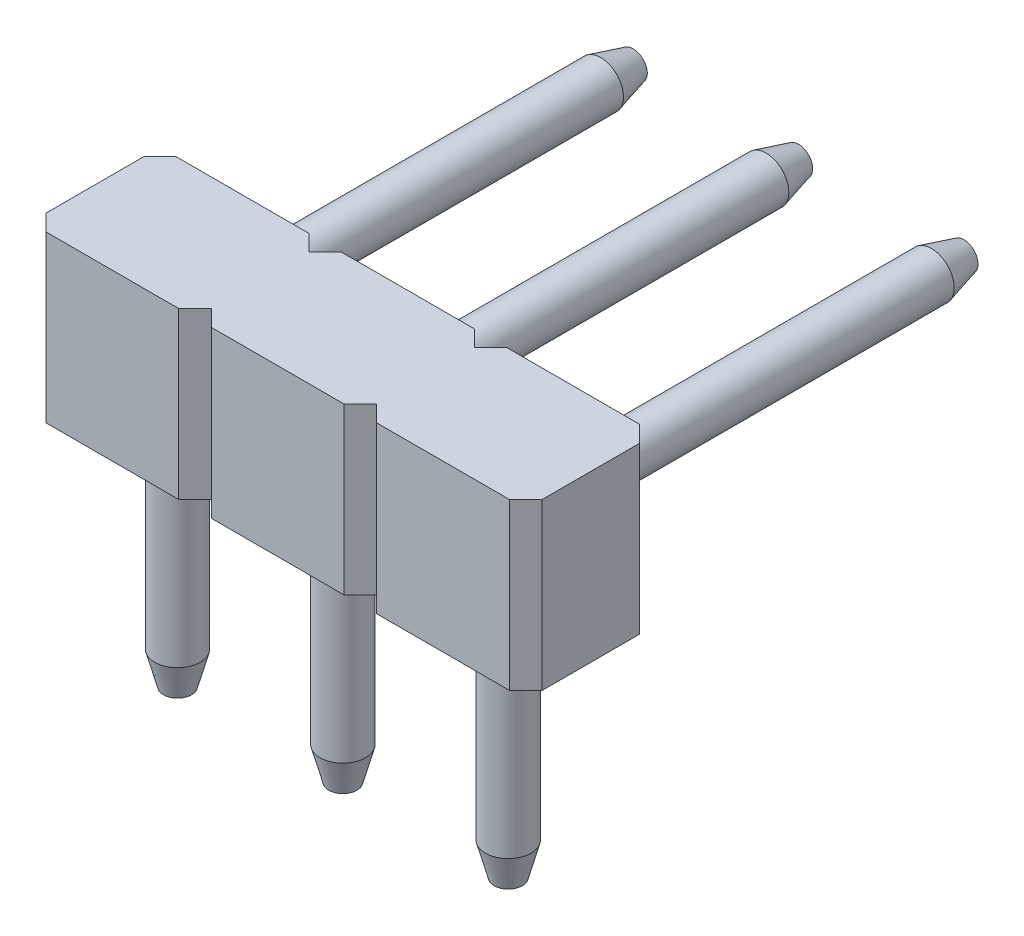
SolidWorks part; units mm, degrees
ref_plane "Plan de face" through (0, 0, 0) normal (0, 0, 1) x (1, 0, 0)
ref_plane "Plan de dessus" through (0, 0, 0) normal (0, 1, 0) x (1, 0, 0)
ref_plane "Plan de droite" through (0, 0, 0) normal (1, 0, 0) x (0, 0, -1)
sketch "Esquisse1" plane through (0, 0, 0) normal (0, 1, 0) x (1, 0, 0)
  circle A0 centre (0, 0) radius 0.35
  circle A1 centre (2.54, 0) radius 0.35
  circle A2 centre (5.08, 0) radius 0.35
  dimension "D1" = 0.7
  dimension "D2" = 3
extrude "Boss.-Extru.1" add sketch "Esquisse1" along normal blind 1 and the other way blind 3.5
chamfer "Chanfrein1" distance 0.5 angle 15 2 edges at (0, 1, 0.35) (0, -3.5, 0.35)
chamfer "Chanfrein2" distance 0.5 angle 15 2 edges at (2.54, -3.5, 0.35) (2.54, 1, 0.35)
chamfer "Chanfrein3" distance 0.5 angle 15 2 edges at (5.08, 1, 0.35) (5.08, -3.5, 0.35)
sketch "Esquisse2" plane through (0, 0, 0) normal (0, 1, 0) x (1, 0, 0)
  line L0 (-1.27, 0.75) -> (-1.02, 1)
  line L1 (-1.02, 1) -> (1.02, 1)
  line L2 (-1.27, 0.75) -> (-1.27, -0.75)
  line L3 (-1.02, -1) -> (1.0167, -1)
  line L5 (1.02, 1) -> (1.27, 0.75)
  line L6 (1.27, -0.75) -> (1.0167, -1)
  line L7 (-1.27, -0.75) -> (-1.02, -1)
  line L8 (1.27, 0.75) -> (1.52, 1)
  line L9 (1.52, 1) -> (3.56, 1)
  line L11 (1.52, -1) -> (3.5567, -1)
  line L13 (3.56, 1) -> (3.81, 0.75)
  line L14 (3.81, -0.75) -> (3.5567, -1)
  line L15 (1.27, -0.75) -> (1.52, -1)
  line L16 (3.81, 0.75) -> (4.06, 1)
  line L17 (4.06, 1) -> (6.1, 1)
  line L19 (4.06, -1) -> (6.0967, -1)
  line L20 (6.35, 0.75) -> (6.35, -0.75)
  line L21 (6.1, 1) -> (6.35, 0.75)
  line L22 (6.35, -0.75) -> (6.0967, -1)
  line L23 (3.81, -0.75) -> (4.06, -1)
  line L25 (3.81, 0.75) -> (3.81, -0.75) [skipped]
  line L26 (1.27, 0.75) -> (1.27, -0.75) [skipped]
  point P0 (-1.27, 1)
  point P1 (1.2667, -1)
  point P2 (-1.27, -1)
  point P3 (1.27, 1)
  point P14 (1.27, 1)
  point P15 (3.8067, -1)
  point P16 (1.27, -1)
  point P17 (3.81, 1)
  point P26 (3.81, 1)
  point P27 (6.3467, -1)
  point P28 (3.81, -1)
  point P29 (6.35, 1)
  dimension "D1" = 1.27
  dimension "D2" = 2.54
  dimension "D3" = 1
  dimension "D4" = 2
  dimension "D5" = 3
extrude "Boss.-Extru.2" add sketch "Esquisse2" along normal blind 2.54
sketch "Esquisse3" plane through (0, 0, -1) normal (0, 0, -1) x (-1, 0, 0)
  line L1 (-6.1, 0) -> (-4.06, 0) construction
  line L2 (-6.35, 2.54) -> (-6.35, 0) construction
  circle A0 centre (-5.08, 1.27) radius 0.35
  circle A1 centre (-2.54, 1.27) radius 0.35
  circle A2 centre (0, 1.27) radius 0.35
  dimension "D1" = 1.27
  dimension "D2" = 1.27
  dimension "D4" = 0.7
  dimension "D3" = 3
extrude "Boss.-Extru.3" add sketch "Esquisse3" along normal blind 6
chamfer "Chanfrein4" distance 0.5 angle 15 3 edges at (2.19, 1.27, -7) (-0.35, 1.27, -7) (4.73, 1.27, -7)
